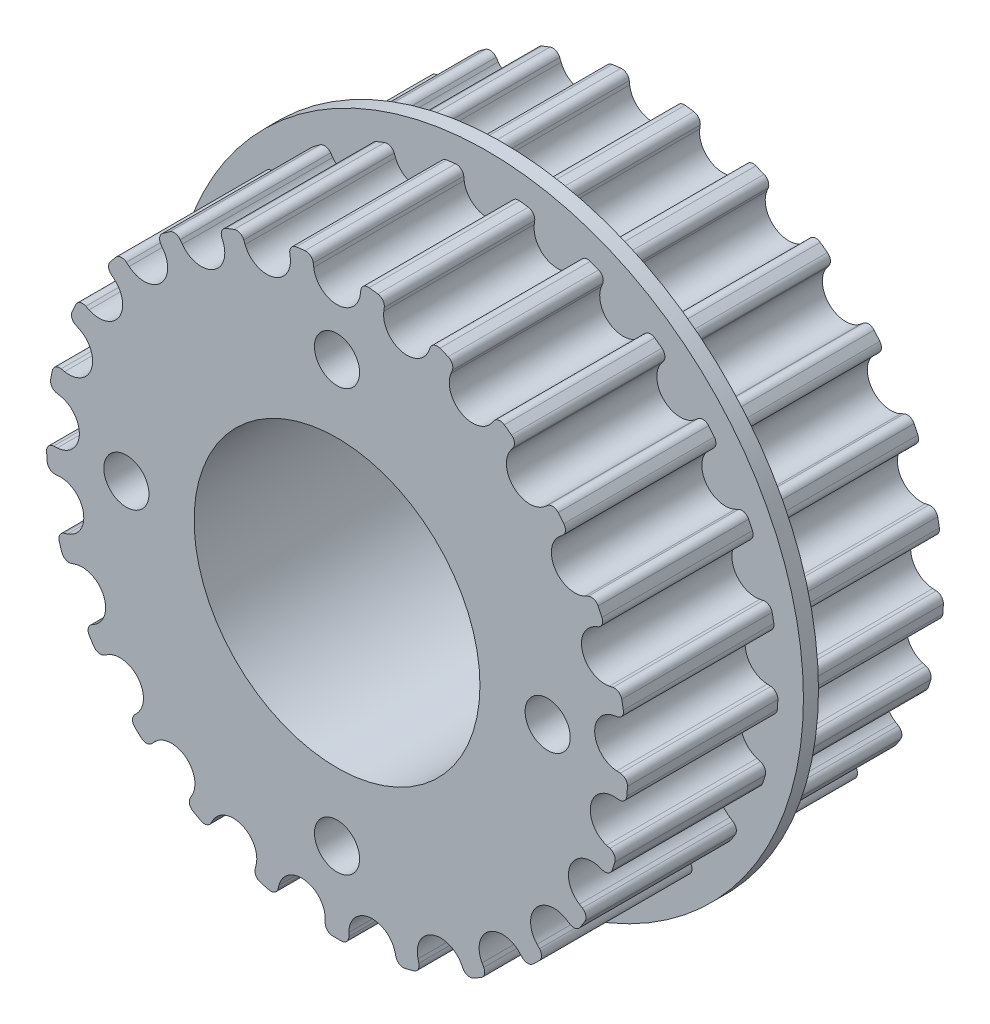
SolidWorks part; units mm, degrees
material "6061 合金"
ref_plane "前视基准面" through (0, 0, 0) normal (0, 0, 1) x (1, 0, 0)
ref_plane "上视基准面" through (0, 0, 0) normal (0, 1, 0) x (1, 0, 0)
ref_plane "右视基准面" through (0, 0, 0) normal (1, 0, 0) x (0, 0, -1)
other "Configuration Table"
sketch "草图1" plane through (0, 0, 0) normal (0, 0, 1) x (1, 0, 0)
  circle A0 centre (0, 0) radius 19.8944
  dimension "P.D" = 39.7887
extrude "凸台-拉伸1" add sketch "草图1" along normal blind 21
sketch "草图2" plane through (0, 0, 21) normal (0, 0, 1) x (1, 0, 0)
  line L0 (0, 19.8944) -> (0, 19.3224) construction
  line L1 (0, 19.3224) -> (0, 0) construction
  line L2 (1.5774, 18.7687) -> (1.5484, 18.5323)
  line L3 (2.4934, 19.7375) -> (2.4217, 19.17)
  line L4 (-2.4934, 19.7375) -> (-2.4217, 19.17)
  line L5 (-1.5774, 18.7687) -> (-1.5484, 18.5323)
  circle A0 centre (0, 0) radius 19.8944 construction
  arc A1 (2.4934, 19.7375) -> (-2.4934, 19.7375) centre (0, 0) ccw
  circle A2 centre (0, 0) radius 19.3224 construction
  arc A3 (-1.5484, 18.5323) -> (1.5484, 18.5323) centre (0, 18.7224) ccw
  arc A4 (2.1288, 19.2047) -> (2.4217, 19.17) centre (0, 0) cw
  arc A5 (1.5774, 18.7687) -> (2.1288, 19.2047) centre (2.0737, 18.7078) cw
  arc A6 (-1.5774, 18.7687) -> (-2.1288, 19.2047) centre (-2.0737, 18.7078) ccw
  arc A7 (-2.1288, 19.2047) -> (-2.4217, 19.17) centre (0, 0) ccw
  point P16 (1.6369, 19.2529)
  point P21 (0, 17.1624)
  dimension "R" = 1.56
  dimension "D3" = 0.5
  dimension "D1" = 7.2
  dimension "D2" = 7
  dimension "H_g" = 2.16
  dimension "delta" = 0.572
extrude "切除-拉伸1" cut sketch "草图2" against normal through all
pattern_circular "阵列(圆周)1" count 25 over 360 about axis through (0, 0, 0) along (0, 0, 1) of "切除-拉伸1"
ref_plane "基准面1" through (0, 0, 11) normal (0, 0, 1) x (1, 0, 0)
sketch "草图3" plane through (0, 0, 21) normal (0, 0, 1) x (1, 0, 0)
  circle A0 centre (0, 0) radius 21
  dimension "D1" = 42
extrude "凸台-拉伸2" add sketch "草图3" against normal blind 1 from surface at -10 starting at plane "基准面1"
sketch "草图4" plane through (0, 0, 21) normal (0, 0, 1) x (1, 0, 0)
  circle A0 centre (0, 0) radius 9.5
  dimension "D1" = 19
extrude "切除-拉伸2" cut sketch "草图4" against normal up to next
sketch "草图5" plane through (0, 0, 21) normal (0, 0, 1) x (1, 0, 0)
  circle A0 centre (14, 0) radius 1.5
  circle A1 centre (14, 0) radius 1.5
  circle A2 centre (14, 0) radius 1.5
  circle A3 centre (14, 0) radius 1.5
  circle A4 centre (0, -14) radius 1.5
  circle A5 centre (-14, 0) radius 1.5
  circle A6 centre (0, 14) radius 1.5
  point P2 (0, 0)
  dimension "D2" = 3
  dimension "D4" = 4
  dimension "D1" = 14
  dimension "D3" = 4
extrude "切除-拉伸3" cut sketch "草图5" against normal up to next contours A6 | A0 | A4 | A5
equation "\"P\"= 5'（勿动）"
equation "\"N\"= 25'齿数（5M不小于13）"
equation "\"H\"= 21'齿厚（一般为带宽+2）"
equation "\"R_t\"= 0.5'齿槽圆角（通常无需修改）"
equation "\"P.D@草图1\"= \"P\" * \"N\" / pi'节径"
equation "\"D1@凸台-拉伸1\"=\"H\""
equation "\"D1@草图2\"= 180 / \"N\"'作者：wister"
equation "\"R@草图2\"= 1.56'齿顶圆角"
equation "\"D3@草图2\"=\"R_t\""
equation "\"D1@阵列(圆周)1\"=\"N\""
equation "\"H_g@草图2\"= 2.16'齿槽深"
equation "\"delta@草图2\"= 1.144 / 2'节顶距"
